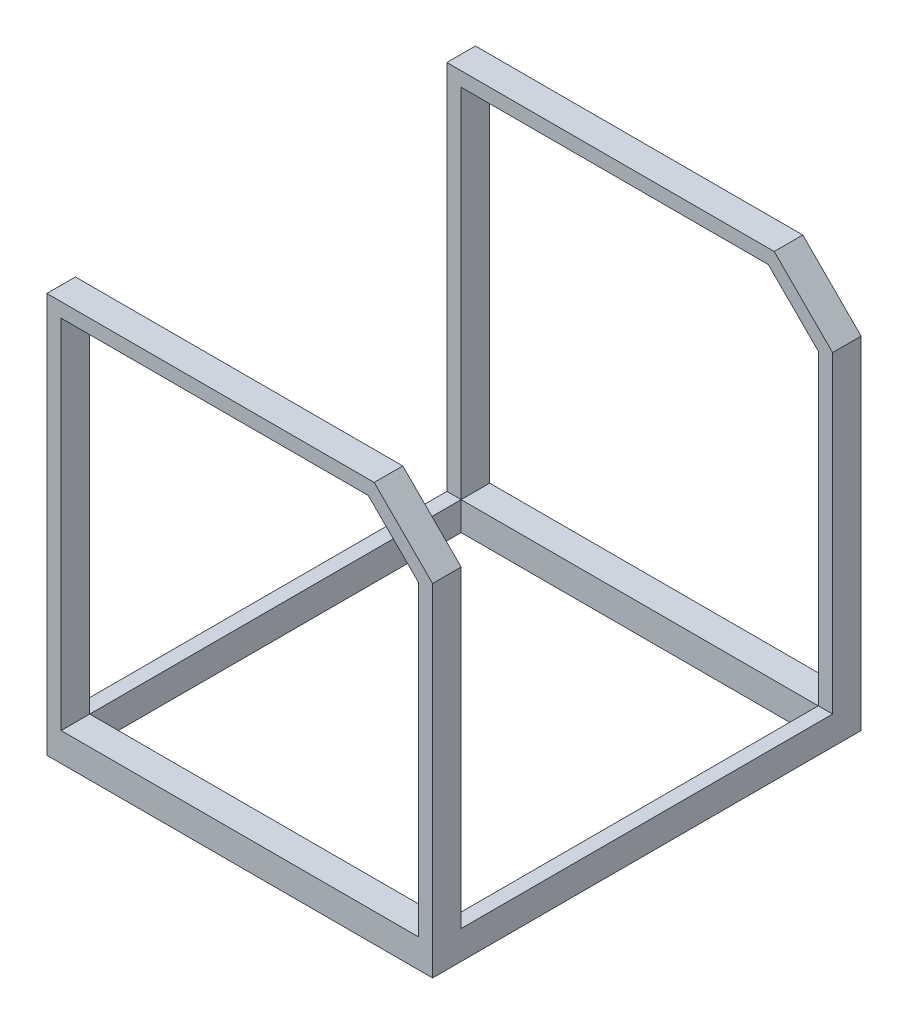
SolidWorks part; units mm, degrees
ref_plane "Front Plane" through (0, 0, 0) normal (0, 0, 1) x (1, 0, 0)
ref_plane "Top Plane" through (0, 0, 0) normal (0, 1, 0) x (1, 0, 0)
ref_plane "Right Plane" through (0, 0, 0) normal (1, 0, 0) x (0, 0, -1)
sketch "Sketch1" plane through (0, 0, 0) normal (0, 0, 1) x (1, 0, 0)
  line L0 (0, 0) -> (0, 560)
  line L1 (0, 560) -> (458.2843, 560)
  line L2 (540, 478.2843) -> (540, 0)
  line L3 (540, 0) -> (0, 0)
  line L4 (20, 40) -> (20, 540)
  line L5 (20, 540) -> (450, 540)
  line L6 (520, 470) -> (520, 40)
  line L7 (520, 40) -> (20, 40)
  line L8 (450, 540) -> (520, 470)
  line L9 (458.2843, 560) -> (540, 478.2843)
  point P4 (540, 560)
  point P8 (520, 540)
  dimension "D1" = 20
  dimension "D2" = 40
  dimension "D3" = 20
  dimension "D4" = 20
  dimension "D5" = 430
  dimension "D6" = 20
  dimension "D8" = 500
extrude "Boss-Extrude1" add sketch "Sketch1" along normal blind 40
sketch "Sketch2" plane through (0, 0, 40) normal (0, 0, 1) x (1, 0, 0)
  line L1 (540, 0) -> (520, 0)
  line L2 (540, 0) -> (540, 40)
  line L3 (540, 40) -> (520, 40)
  line L4 (520, 0) -> (520, 40)
  line L5 (0, 0) -> (20, 0)
  line L6 (0, 0) -> (0, 40)
  line L7 (0, 40) -> (20, 40)
  line L8 (20, 0) -> (20, 40)
extrude "Boss-Extrude2" add sketch "Sketch2" along normal blind 520
ref_plane "Plane1" through (0, 0, 300) normal (0, 0, -1) x (-1, 0, 0)
mirror "Mirror1" about plane through (0, 0, 300) normal (0, 0, -1) of "Boss-Extrude1"
